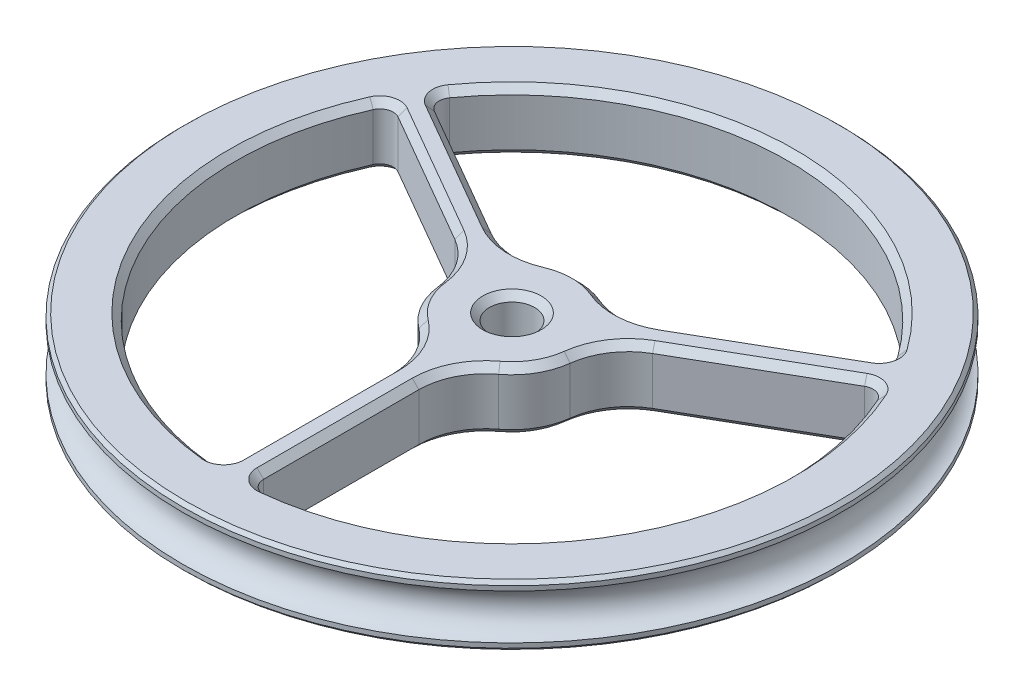
SolidWorks part; units mm, degrees
ref_plane "Front" through (0, 0, 0) normal (0, 0, 1) x (1, 0, 0)
ref_plane "Top" through (0, 0, 0) normal (0, 1, 0) x (1, 0, 0)
ref_plane "Right" through (0, 0, 0) normal (1, 0, 0) x (0, 0, -1)
sketch "Sketch1" plane through (0, 0, 0) normal (0, 1, 0) x (1, 0, 0)
  circle A0 centre (0, 0) radius 24.765
  dimension "D1" = 49.53
extrude "Boss-Extrude1" add sketch "Sketch1" along normal mid plane 4.572
sketch "Sketch2" plane through (0, 0, 0) normal (1, 0, 0) x (0, 0, -1)
  line L0 (0, 0) -> (0, 2.286) construction
  line L2 (0, 0) -> (25.065, 0) construction
  line L3 (24.765, -2.286) -> (24.765, 2.286) construction
  line L4 (24.765, 2.286) -> (-24.765, 2.286) construction
  circle A0 centre (25.065, 0) radius 1.7145
  dimension "D1" = 3.429
  dimension "D2" = 0.3
revolve "Cut-Revolve1" cut sketch "Sketch2" angle 360 about L0
sketch "Sketch3" plane through (0, 2.286, 0) normal (0, 1, 0) x (1, 0, 0)
  circle A0 centre (0, 0) radius 1.7
  dimension "D2" = 3.4
extrude "Cut-Extrude1" cut sketch "Sketch3" against normal through all contours A0
sketch "Sketch4" plane through (0, 2.286, 0) normal (0, 1, 0) x (1, 0, 0)
  line L0 (0, 0) -> (21.4471, 12.3825) construction
  line L1 (0, 0) -> (0, 24.765) construction
  line L2 (0, 0) -> (-21.4471, 12.3825) construction
  line L3 (3.7426, 3.3155) -> (17.4622, 11.2365)
  line L4 (-3.7426, 3.3155) -> (-17.4622, 11.2365)
  circle A0 centre (0, 0) radius 24.765 construction
  arc A1 (-3.7426, 3.3155) -> (3.7426, 3.3155) centre (0, 0) cw
  arc A3 (-17.4622, 11.2365) -> (17.4622, 11.2365) centre (0, 0) cw
  dimension "D2" = 4
  dimension "D3" = 5
  dimension "D1" = 120
  dimension "D4" = 2
extrude "Cut-Extrude2" cut sketch "Sketch4" against normal through all
pattern_circular "CirPattern1" count 3 every 120 about axis through (0, 0, 0) along (0, 1, 0) of "Cut-Extrude2"
fillet "Fillet1" radius 5 6 edges at (3.7426, 0, -3.3155) (-3.7426, 0, -3.3155) (4.7426, 0, -1.5835) (1, 0, 4.899) (-1, 0, 4.899) (-4.7426, 0, -1.5835)
fillet "Fillet4" radius 1 6 edges at (17.4622, 0, -11.2365) (18.4622, 0, -9.5044) (-18.4622, 0, -9.5044) (-17.4622, 0, -11.2365) (1, 0, 20.7409) (-1, 0, 20.7409)
chamfer "Chamfer1" distance 0.5 angle 45 2 edges at (0, -2.286, 1.7) (0, 2.286, 1.7)
chamfer "Chamfer2" distance 0.5 angle 45 48 edges at (-1, -2.286, 13.8318) (-4.3301, -2.286, 2.5) (-12.4787, -2.286, -6.0499) (-17.983, -2.286, 10.3825) (-11.4787, -2.286, -7.7819) (0, -2.286, -5) (0, -2.286, -20.765) (11.4787, -2.286, -7.7819) (17.983, -2.286, 10.3825) (12.4787, -2.286, -6.0499) (4.3301, -2.286, 2.5) (1, -2.286, 13.8318) (17.983, 2.286, 10.3825) (1, 2.286, 13.8318) (4.3301, 2.286, 2.5) (12.4787, 2.286, -6.0499) (0, 2.286, -20.765) (11.4787, 2.286, -7.7819) (0, 2.286, -5) (-11.4787, 2.286, -7.7819) (-17.983, 2.286, 10.3825) (-1, 2.286, 13.8318) (-4.3301, 2.286, 2.5) (-12.4787, 2.286, -6.0499) (-5.7556, -2.286, -1.5588) (-1.5279, -2.286, 5.7639) (-18.3366, -2.286, -9.0513) (-1.3296, -2.286, 20.4056) (-4.2278, -2.286, -4.2051) (-17.0069, -2.286, -11.3543) (4.2278, -2.286, -4.2051) (17.0069, -2.286, -11.3543) (5.7556, -2.286, -1.5588) (18.3366, -2.286, -9.0513) (1.5279, -2.286, 5.7639) (1.3296, -2.286, 20.4056) (1.3296, 2.286, 20.4056) (1.5279, 2.286, 5.7639) (18.3366, 2.286, -9.0513) (5.7556, 2.286, -1.5588) (17.0069, 2.286, -11.3543) (4.2278, 2.286, -4.2051) (-17.0069, 2.286, -11.3543) (-4.2278, 2.286, -4.2051) (-1.5279, 2.286, 5.7639) (-1.3296, 2.286, 20.4056) (-5.7556, 2.286, -1.5588) (-18.3366, 2.286, -9.0513)
chamfer "Chamfer3" distance 0.25 angle 45 2 edges at (0, -2.286, 24.765) (0, 2.286, 24.765)
